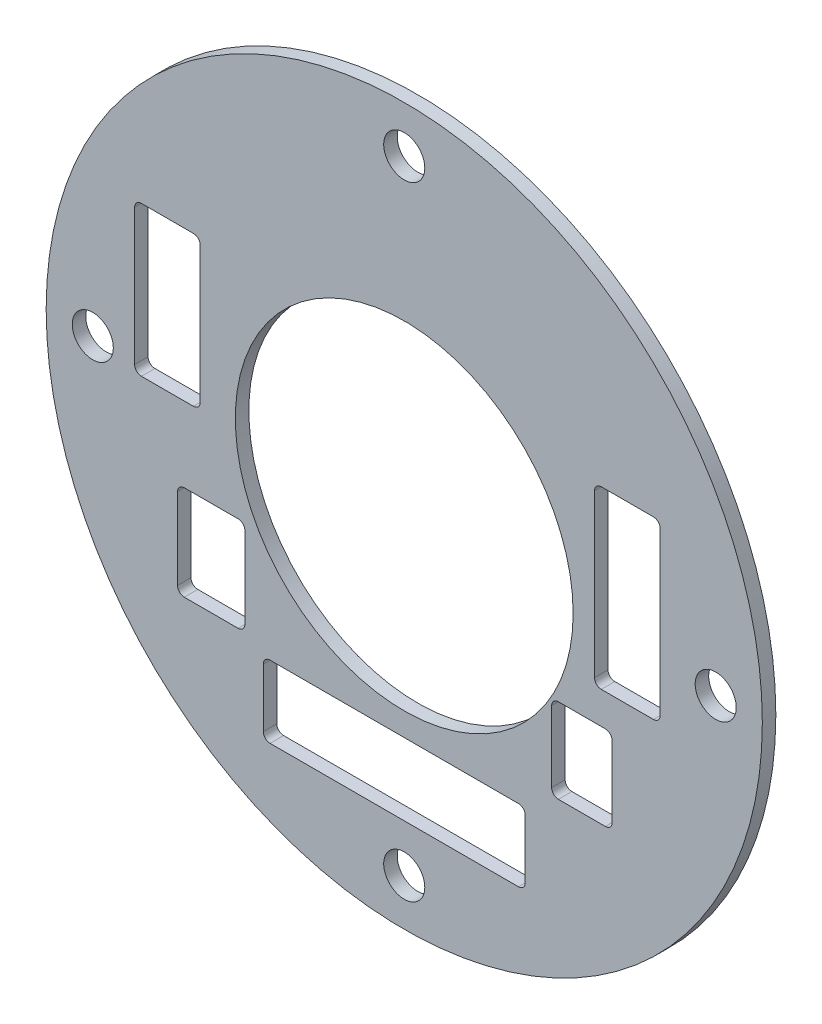
SolidWorks part; units mm, degrees
material "POM 乙缩醛共聚物"
ref_plane "前视基准面" through (0, 0, 0) normal (0, 0, 1) x (1, 0, 0)
ref_plane "上视基准面" through (0, 0, 0) normal (0, 1, 0) x (1, 0, 0)
ref_plane "右视基准面" through (0, 0, 0) normal (1, 0, 0) x (0, 0, -1)
sketch "草图1" plane through (0, 0, 0) normal (0, 0, 1) x (1, 0, 0)
  circle A0 centre (0, 0) radius 12.5
  circle A1 centre (0, 0) radius 26.5
extrude "凸台-拉伸1" add sketch "草图1" along normal blind 1
sketch "草图2" plane through (22.804, -9.3503, -2.5) normal (0, 0, 1) x (1, 0, 0)
  line L0 (-38.402, 19.6523) -> (-42.258, 19.6523)
  line L25 (-42.758, 19.1523) -> (-42.758, 9.0733)
  line L26 (-38.402, 8.5733) -> (-42.258, 8.5733)
  line L27 (-37.902, 19.1523) -> (-37.902, 9.0733)
  line L28 (-8.222, 18.5093) -> (-4.366, 18.5093)
  line L29 (-3.866, 18.0093) -> (-3.866, 6.0253)
  line L30 (-8.222, 5.5253) -> (-4.366, 5.5253)
  line L31 (-8.722, 18.0093) -> (-8.722, 6.0253)
  line L36 (-32.733, -4.8587) -> (-14.352, -4.8587)
  line L37 (-13.852, -5.3587) -> (-13.852, -9.6907)
  line L38 (-32.733, -10.1907) -> (-14.352, -10.1907)
  line L39 (-33.233, -5.3587) -> (-33.233, -9.6907)
  line L40 (-35.1, 3.0153) -> (-39.083, 3.0153)
  line L41 (-39.583, 2.5153) -> (-39.583, -3.4997)
  line L42 (-35.1, -3.9997) -> (-39.083, -3.9997)
  line L43 (-34.6, 2.5153) -> (-34.6, -3.4997)
  line L44 (-11.397, 3.1423) -> (-7.922, 3.1423)
  line L45 (-7.422, 2.6423) -> (-7.422, -2.6107)
  line L46 (-11.397, -3.1107) -> (-7.922, -3.1107)
  line L47 (-11.897, 2.6423) -> (-11.897, -2.6107)
  arc A0 (-38.402, 19.6523) -> (-37.902, 19.1523) centre (-38.402, 19.1523) cw
  arc A1 (-42.258, 19.6523) -> (-42.758, 19.1523) centre (-42.258, 19.1523) ccw
  arc A2 (-42.758, 9.0733) -> (-42.258, 8.5733) centre (-42.258, 9.0733) ccw
  arc A3 (-38.402, 8.5733) -> (-37.902, 9.0733) centre (-38.402, 9.0733) ccw
  arc A4 (-39.583, -3.4997) -> (-39.083, -3.9997) centre (-39.083, -3.4997) ccw
  arc A5 (-39.083, 3.0153) -> (-39.583, 2.5153) centre (-39.083, 2.5153) ccw
  arc A6 (-35.1, 3.0153) -> (-34.6, 2.5153) centre (-35.1, 2.5153) cw
  arc A7 (-35.1, -3.9997) -> (-34.6, -3.4997) centre (-35.1, -3.4997) ccw
  arc A8 (-32.733, -4.8587) -> (-33.233, -5.3587) centre (-32.733, -5.3587) ccw
  arc A9 (-32.733, -10.1907) -> (-33.233, -9.6907) centre (-32.733, -9.6907) cw
  arc A10 (-13.852, -9.6907) -> (-14.352, -10.1907) centre (-14.352, -9.6907) cw
  arc A11 (-14.352, -4.8587) -> (-13.852, -5.3587) centre (-14.352, -5.3587) cw
  arc A12 (-7.422, -2.6107) -> (-7.922, -3.1107) centre (-7.922, -2.6107) cw
  arc A13 (-11.397, -3.1107) -> (-11.897, -2.6107) centre (-11.397, -2.6107) cw
  arc A14 (-11.397, 3.1423) -> (-11.897, 2.6423) centre (-11.397, 2.6423) ccw
  arc A15 (-7.922, 3.1423) -> (-7.422, 2.6423) centre (-7.922, 2.6423) cw
  arc A16 (-3.866, 6.0253) -> (-4.366, 5.5253) centre (-4.366, 6.0253) cw
  arc A17 (-8.222, 5.5253) -> (-8.722, 6.0253) centre (-8.222, 6.0253) cw
  arc A18 (-8.222, 18.5093) -> (-8.722, 18.0093) centre (-8.222, 18.0093) ccw
  arc A19 (-4.366, 18.5093) -> (-3.866, 18.0093) centre (-4.366, 18.0093) cw
  dimension "D1" = 0.5
extrude "切除-拉伸1" cut sketch "草图2" against normal up to next from surface
sketch "草图3" plane through (22.804, -9.3503, -2.5) normal (0, 0, 1) x (1, 0, 0)
  circle A0 centre (-22.804, 32.4003) radius 1.52
  circle A1 centre (-45.854, 9.3503) radius 1.52
  circle A2 centre (-22.804, -13.6997) radius 1.52
  circle A3 centre (0.246, 9.3503) radius 1.52
extrude "切除-拉伸2" cut sketch "草图3" against normal up to next from surface
